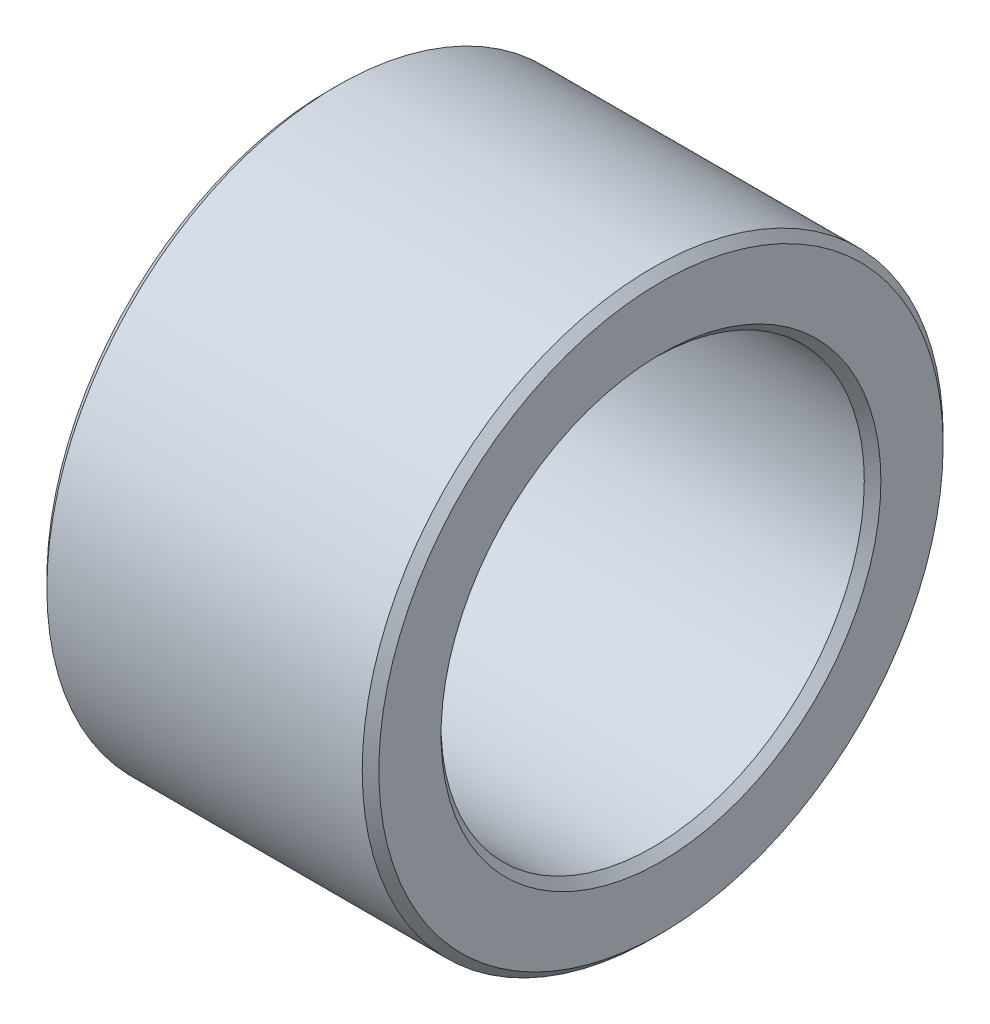
SolidWorks part; units mm, degrees
other "标注1"
sketch "草图2" plane through (0, 3.5, -3.5) normal (-0.2968, 0.4965, -0.8157) x (0.5922, -0.5744, -0.5651)
other "标注2"
sketch "草图3" plane through (0, 3.5, -3.5) normal (-0.2968, 0.4965, -0.8157) x (0.5922, -0.5744, -0.5651)
material "黄铜"
ref_plane "前视基准面" through (0, 0, 0) normal (1, 0, 0) x (0, 1, 0)
ref_plane "上视基准面" through (0, 0, 0) normal (0, 0, 1) x (0, 1, 0)
ref_plane "右视基准面" through (0, 0, 0) normal (0, 1, 0) x (-1, 0, 0)
other "Configuration Table"
sketch "草图1" plane through (0, 0, 0) normal (1, 0, 0) x (0, 1, 0)
  circle A0 centre (0, 0) radius 3.5
  circle A1 centre (0, 0) radius 2.55
  dimension "D1" = 7
  dimension "D2" = 5.1
extrude "凸台-拉伸1" add sketch "草图1" along normal blind 4
chamfer "倒角1" distance 0.1 angle 45 4 edges at (4, 0, -2.55) (0, 0, -2.55) (0, 0, -3.5) (4, 0, -3.5)
